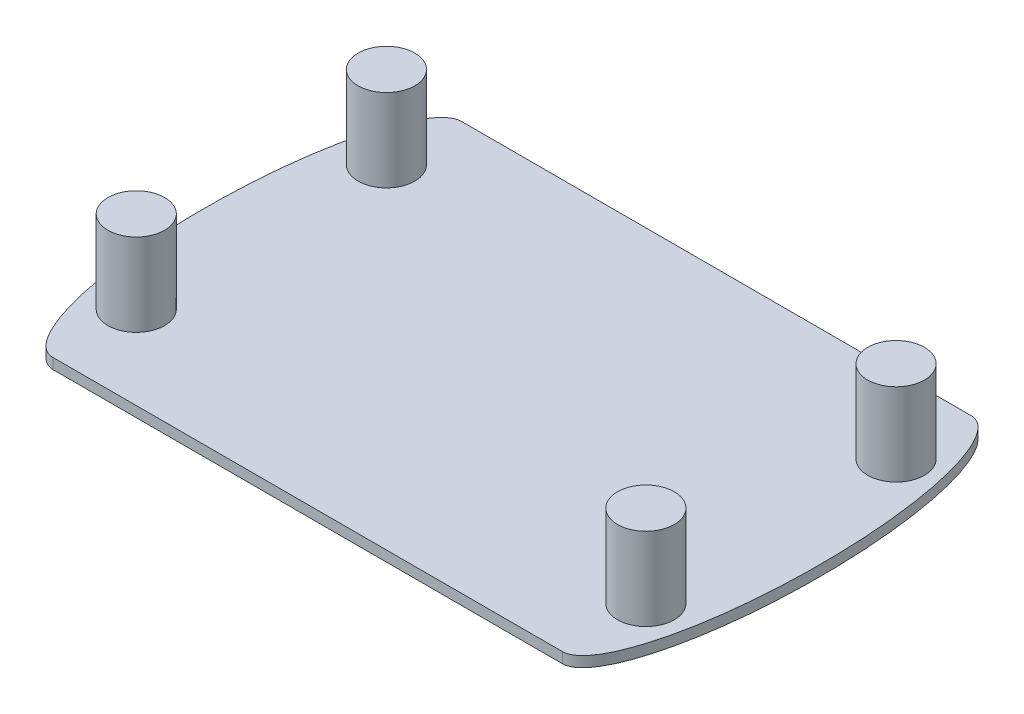
SolidWorks part; units mm, degrees
ref_plane "Plano frontal" through (0, 0, 0) normal (0, 0, 1) x (1, 0, 0)
ref_plane "Plano superior" through (0, 0, 0) normal (0, 1, 0) x (1, 0, 0)
ref_plane "Plano direito" through (0, 0, 0) normal (1, 0, 0) x (0, 0, -1)
sketch "Esboço1" plane through (0, 0, 0) normal (0, 1, 0) x (1, 0, 0)
  line L0 (0, 0) -> (0, 26.3461) construction
  circle A0 centre (-30.55, 30) radius 3.4
  circle A1 centre (-30.55, 0) radius 3.4
  circle A2 centre (30.55, 0) radius 3.4
  circle A3 centre (30.55, 30) radius 3.4
  dimension "D1" = 6.8
  dimension "D2" = 30.55
  dimension "D3" = 30
  dimension "D4" = 0
extrude "Ressalto-extrusão1" add sketch "Esboço1" along normal blind 9.9
sketch "Esboço3" plane through (0, 0, 0) normal (0, 1, 0) x (1, 0, 0)
  line L0 (-30.55, -10) -> (30.55, -10)
  line L1 (0, 0) -> (0, 17.2432) construction
  line L2 (-30.55, 39) -> (30.55, 39)
  line L3 (-30.55, 39) -> (-30.55, -10)
  line L4 (30.55, 39) -> (30.55, -10)
  circle A0 centre (-30.55, 0) radius 3.4 construction
  circle A1 centre (-30.55, 30) radius 3.4 construction
  ellipse E0 centre (-30.55, 14.5) end of major axis (-30.55, 39) minor radius 6.4006
  ellipse E1 centre (30.55, 14.5) end of major axis (30.55, 39) minor radius 6.4006
  point P6 (0, -10)
  point P25 (0, 39)
  dimension "D2" = 10
  dimension "D3" = 9
  dimension "D1" = 30.55
  dimension "D4" = 6.4006
extrude "Ressalto-extrusão2" add sketch "Esboço3" against normal blind 1.26
